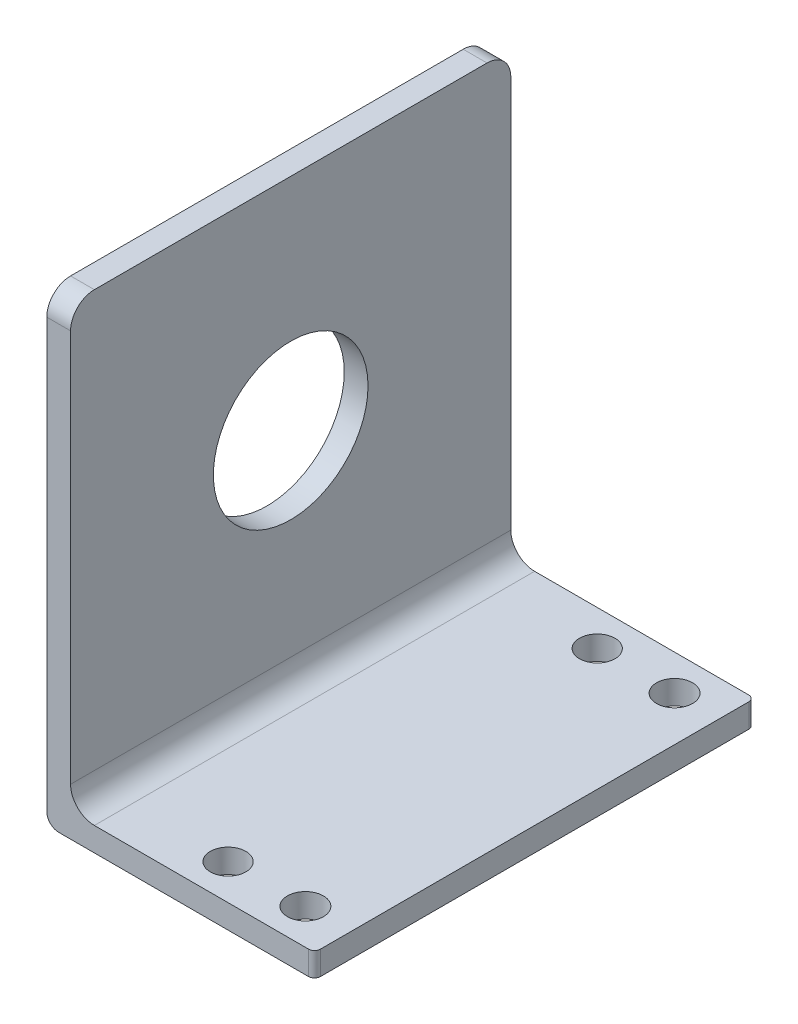
SolidWorks part; units mm, degrees
ref_plane "Front Plane" through (0, 0, 0) normal (0, 0, 1) x (1, 0, 0)
ref_plane "Top Plane" through (0, 0, 0) normal (0, 1, 0) x (1, 0, 0)
ref_plane "Right Plane" through (0, 0, 0) normal (1, 0, 0) x (0, 0, -1)
sketch "Sketch1" plane through (0, 0, 0) normal (0, 0, 1) x (1, 0, 0)
  line L0 (0, 0) -> (0, 37)
  line L1 (-2, 37) -> (-2, -1)
  line L2 (-1, -2) -> (20.5, -2)
  line L3 (20.5, 0) -> (0, 0)
  line L4 (-2, 37) -> (0, 37)
  line L5 (20.5, -2) -> (20.5, 0)
  arc A0 (-2, -1) -> (-1, -2) centre (-1, -1) ccw
  point P9 (-2, -2)
  dimension "D1" = 2
  dimension "D4" = 1
  dimension "D2" = 22.5
  dimension "D3" = 39
  dimension "D5" = 2
extrude "Boss-Extrude1" add sketch "Sketch1" along normal blind 37 contours L0 L4 L1 A0 L2 L5 L3
sketch "Sketch2" plane through (0, 0, 0) normal (1, 0, 0) x (0, 0, -1)
  line L0 (-18.5, 37) -> (-18.5, 0) construction
  line L1 (-37, 37) -> (0, 37) construction
  line L2 (-37, 0) -> (0, 0) construction
  line L4 (0, 0) -> (0, 37) construction
  line L5 (0, 18.5) -> (-37, 18.5) construction
  line L6 (-37, 0) -> (-37, 37) construction
  circle A0 centre (-18.5, 18.5) radius 6.5
  circle A1 centre (-18.5, 9) radius 1.5
  dimension "D1" = 9
extrude "Cut-Extrude1" cut sketch "Sketch2" against normal blind 10
sketch "Sketch3" plane through (0, 0, 0) normal (0, 1, 0) x (1, 0, 0)
  line L0 (10.25, 0) -> (10.25, -37) construction
  line L1 (20.5, 0) -> (0, 0) construction
  line L2 (20.5, -37) -> (0, -37) construction
  line L4 (20.5, -18.5) -> (0, -18.5) construction
  line L5 (20.5, -37) -> (20.5, 0) construction
  line L6 (0, -37) -> (0, 0) construction
  circle A0 centre (16.75, -2.987) radius 1.5138
  circle A1 centre (10.25, -2.987) radius 1.4952
  circle A2 centre (4, -2.987) radius 1.4952
  circle A3 centre (16.75, -34.013) radius 1.5138
  circle A4 centre (10.25, -34.013) radius 1.4952
  circle A5 centre (4, -34.013) radius 1.4952
  dimension "D2" = 6.5
extrude "Cut-Extrude2" cut sketch "Sketch3" against normal blind 10
fillet "Fillet1" radius 2 2 edges at (-1, 37, 0) (-1, 37, 37)
fillet "Fillet3" radius 0.5 2 edges at (20.5, -1, 0) (20.5, -1, 37)
sketch "Sketch5" plane through (0, 0, 0) normal (0, 1, 0) x (1, 0, 0)
  line L0 (20, -37) -> (0, -37) construction
  line L1 (0, 0) -> (7.1449, 0)
  line L2 (0, 0) -> (0, -37)
  line L3 (0, -37) -> (7.1449, -37)
  line L4 (7.1449, 0) -> (7.1449, -37)
extrude "Boss-Extrude3" add sketch "Sketch5" against normal blind 2
sketch "Sketch6" plane through (0, 0, 0) normal (1, 0, 0) x (0, 0, -1)
  circle A0 centre (-18.5, 9) radius 2.3427
extrude "Boss-Extrude4" add sketch "Sketch6" against normal blind 2
fillet "Fillet5" radius 2 1 edges at (0, 0, 18.5)
